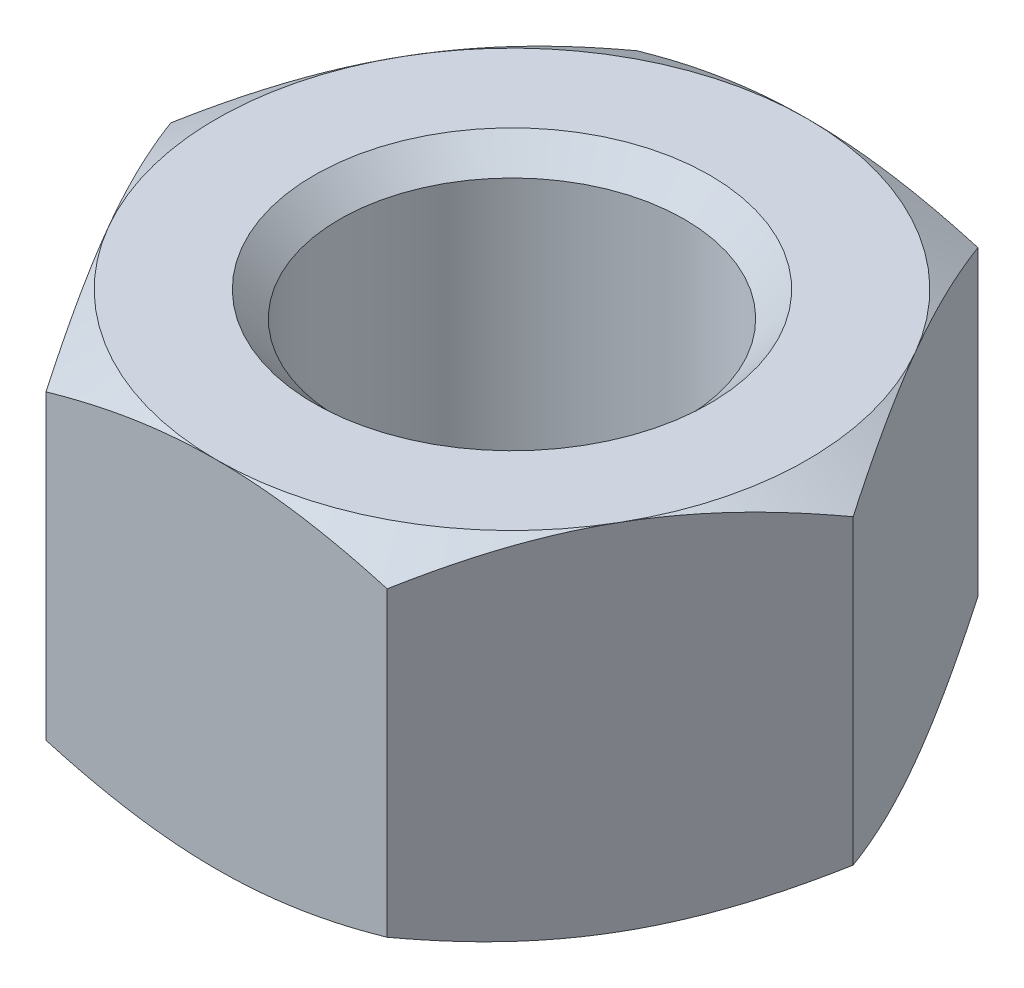
SolidWorks part; units mm, degrees
material "1.0050 (E295)"
ref_plane "Спереди" through (0, 0, 0) normal (0, 0, 1) x (1, 0, 0)
ref_plane "Сверху" through (0, 0, 0) normal (0, 1, 0) x (1, 0, 0)
ref_plane "Справа" through (0, 0, 0) normal (1, 0, 0) x (0, 0, -1)
sketch "Эскиз1" plane through (0, 0, 0) normal (0, 1, 0) x (1, 0, 0)
  line L1 (-5.1962, 9) -> (-10.3923, 0)
  line L2 (-10.3923, 0) -> (-5.1962, -9)
  line L3 (-5.1962, -9) -> (5.1962, -9)
  line L4 (5.1962, -9) -> (10.3923, 0)
  line L5 (10.3923, 0) -> (5.1962, 9)
  line L6 (5.1962, 9) -> (-5.1962, 9)
  circle A0 centre (0, 0) radius 9 construction
  dimension "D1" = 18
extrude "Бобышка-Вытянуть1" add sketch "Эскиз1" along normal blind 10.8
sketch "Эскиз2" plane through (0, 0, 0) normal (1, 0, 0) x (0, 0, -1)
  line L0 (-9, 10.8) -> (-10.47, 10.8)
  line L1 (-10.47, 10.8) -> (-10.47, 9.9513)
  line L2 (-10.47, 9.9513) -> (-9, 10.8)
  line L3 (0, -1000) -> (0, 49000) construction
  line L4 (-9, 0) -> (-10.47, 0)
  line L5 (-10.47, 0) -> (-10.47, 0.8487)
  line L6 (-10.47, 0.8487) -> (-9, 0)
  dimension "D1" = 30
  dimension "D2" = 1.47
  dimension "D3" = 30
revolve "Вырез-Повернуть1" cut sketch "Эскиз2" angle 360 about L3
hole_wizard "Отверстие обработанное метчиком M12x1.51" positions "Трехмерный эскиз1" profile "Эскиз3" tap size "M12x1.5" standard "Ansi Metric" end condition through all
sketch3d "Трехмерный эскиз1"
  point P0 (0, 0, 0)
  point P4 (0, 0, 0)
sketch "Эскиз3" plane through (0, 0, 0) normal (1, 0, 0) x (0, 0, -1)
  line L0 (0, 0) -> (0, 10.8)
  line L1 (0, 10.8) -> (6.025, 10.8)
  line L2 (5.25, 10.025) -> (5.25, 0.775)
  line L3 (5.25, 0.775) -> (6.025, 0)
  line L5 (6.025, 0) -> (0, 0)
  line L6 (-5.25, 0.775) -> (-6.025, 0) construction
  line L7 (6.025, 10.8) -> (5.25, 10.025)
  line L8 (-6.025, 10.8) -> (-5.25, 10.025) construction
  line L11 (0, -6.35) -> (0, 107.95) construction
  dimension "Диаметр проходного сверла" = 10.5
  dimension "Глубина проходного сверла" = 10.8
  dimension "Диаметр передней зенковки" = 12.05
  dimension "Угол передней зенковки" = 90
  dimension "Диаметр задней зенковки" = 12.05
  dimension "Угол задней зенковки" = 90
cosmetic thread "Отверстие резьбы1" parameters "D2"=12
cosmetic thread "Отверстие резьбы2" parameters "D2"=12
